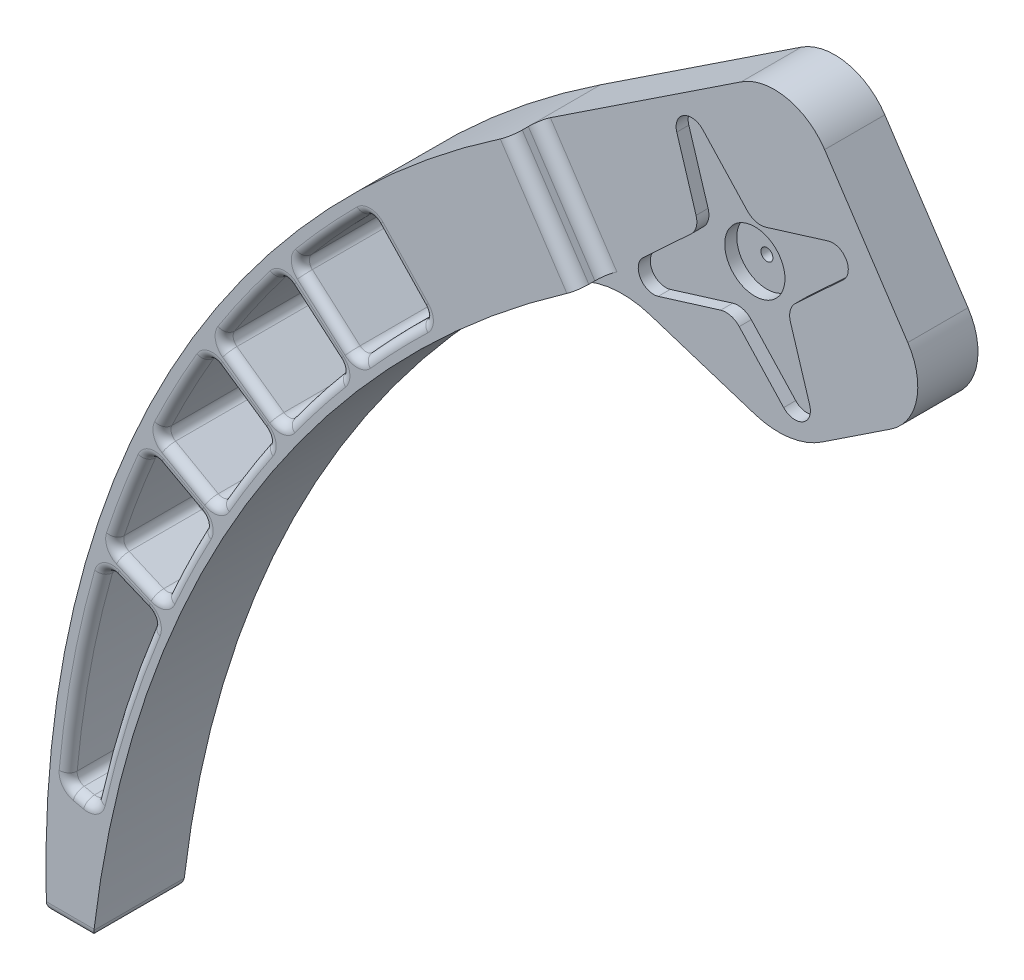
SolidWorks part; units mm, degrees
ref_plane "Plan de face" through (0, 0, 0) normal (0, 0, 1) x (1, 0, 0)
ref_plane "Plan de dessus" through (0, 0, 0) normal (0, 1, 0) x (1, 0, 0)
ref_plane "Plan de droite" through (0, 0, 0) normal (1, 0, 0) x (0, 0, -1)
sketch "Esquisse1" plane through (0, 0, 0) normal (0, 0, 1) x (1, 0, 0)
  line L0 (0, 0) -> (-7.7116, 0)
  line L1 (-7.7116, 0) -> (-7.7116, 150) construction
  line L2 (-7.7116, 150) -> (69.2884, 150) construction
  line L3 (69.2884, 150) -> (80.3349, 133.3274)
  arc A0 (-7.7116, 0) -> (69.2884, 150) centre (164.4344, 6.3951) cw
  arc A1 (80.3349, 133.3274) -> (0, 0) centre (185.1203, -20.676) ccw
  dimension "D1" = 20
  dimension "D2" = 150
  dimension "D3" = 77
extrude "Boss.-Extru.1" add sketch "Esquisse1" along normal blind 15
sketch "Esquisse2" plane through (0, 0, 15) normal (0, 0, 1) x (1, 0, 0)
  line L0 (80.3349, 133.3274) -> (69.2884, 150) construction
  line L1 (-7.7116, 0) -> (0, 0) construction
  line L2 (62.3684, 141.3979) -> (70.9664, 130.2035)
  line L3 (48.6033, 129.7481) -> (58.0983, 119.3958)
  line L4 (70.9454, 147.4991) -> (78.6779, 135.8283)
  line L5 (46.0039, 127.2473) -> (55.6406, 117.1018)
  line L6 (69.2884, 150) -> (70.9454, 147.4991)
  line L7 (78.6779, 135.8283) -> (80.3349, 133.3274)
  line L8 (-7.7116, 0) -> (-4.7116, 0)
  line L9 (-3, 0) -> (-4.7116, 0)
  line L10 (0, 0) -> (-3, 0)
  line L11 (33.8448, 113.9602) -> (43.9728, 105.0081)
  line L12 (31.5886, 111.1559) -> (41.7683, 102.4698)
  line L13 (21.2433, 96.4806) -> (31.4285, 89.2228)
  line L14 (19.3677, 93.4257) -> (29.5014, 86.4679)
  line L15 (10.9988, 77.6405) -> (20.603, 72.2126)
  line L16 (9.5313, 74.393) -> (18.9744, 69.2715)
  line L17 (3.2521, 57.7957) -> (11.6148, 54.1641)
  line L18 (2.2102, 54.4164) -> (10.3026, 51.0688)
  line L19 (-4.2431, 20.0283) -> (0.2206, 19.0409)
  arc A1 (78.6779, 135.8283) -> (-3, 0) centre (188.3019, -22.5641) ccw
  arc A2 (70.9454, 147.4991) -> (-4.7116, 0) centre (165.108, 6.0472) ccw
  arc A3 (69.2884, 150) -> (-7.7116, 0) centre (164.4344, 6.3951) ccw
  arc A4 (69.2884, 150) -> (-7.7116, 0) centre (164.4344, 6.3951) ccw construction
  arc A5 (0, 0) -> (80.3349, 133.3274) centre (185.1203, -20.676) cw
  point P0 (78.6779, 135.8283)
  point P1 (70.9454, 147.4991)
  point P4 (-4.7116, 0)
  point P5 (-3, 0)
  dimension "D13" = 1
  dimension "D14" = 5
  dimension "D15" = 1
  dimension "D1" = 3
  dimension "D2" = 3
  dimension "D3" = 3
  dimension "D4" = 3
  dimension "D5" = 4
  dimension "D6" = 5
  dimension "D7" = 1
  dimension "D8" = 5
  dimension "D9" = 1
  dimension "D10" = 5
  dimension "D11" = 1
  dimension "D12" = 5
  dimension "D16" = 10
extrude "Enlèv. mat.-Extru.3" cut sketch "Esquisse2" against normal up to next contours L2 A2 L3 A1 | L5 A2 L11 A1 | L12 A2 L13 A1 | L14 A2 L15 A1 | L16 A2 L17 A1 | L18 A2 L19 A1
sketch "Esquisse12" plane through (0, 0, 0) normal (0, 0, 1) x (1, 0, 0)
  line L0 (94.143, 112.4867) -> (69.2884, 150)
  line L1 (69.2884, 150) -> (110.9699, 177.6162)
  line L2 (110.9699, 177.6162) -> (135.8245, 140.1029)
  line L3 (135.8245, 140.1029) -> (94.143, 112.4867)
  dimension "D1" = 50
  dimension "D2" = 45
  dimension "D3" = 0
extrude "Boss.-Extru.4" add sketch "Esquisse12" along normal blind 10
sketch "Esquisse27" plane through (0, 0, 15) normal (0, 0, 1) x (1, 0, 0)
  line L0 (47.1881, 129.6841) -> (58.0565, 117.812)
  line L1 (58.0565, 117.812) -> (72.7204, 130.1897)
  line L2 (72.7204, 130.1897) -> (62.3562, 143.5699)
  line L3 (62.3562, 143.5699) -> (47.1881, 129.6841)
extrude "Boss.-Extru.5" add sketch "Esquisse27" against normal blind 15
fillet "Congé8" radius 10 2 edges at (135.8245, 140.1029, 5) (110.9699, 177.6162, 5)
fillet "Congé18" radius 2 1 edges at (74.8117, 141.6637, 10)
sketch "Esquisse24" plane through (82.6638, -34.6024, 10) normal (0, 0, 1) x (0.866, 0.5, 0)
  line L0 (107.5945, 145.7269) -> (90.416, 145.7269) construction
  line L1 (89.8462, 148.2269) -> (107.3962, 152.2269)
  line L2 (107.3962, 139.2269) -> (89.8462, 143.2269)
  arc A0 (107.3962, 139.2269) -> (107.3962, 152.2269) centre (107.5945, 145.7269) ccw
  arc A1 (89.8462, 148.2269) -> (89.8462, 143.2269) centre (90.416, 145.7269) ccw
  dimension "D1" = 18
  dimension "D2" = 13
  dimension "D3" = 5
extrude "Enlèv. mat.-Extru.9" cut sketch "Esquisse24" against normal blind 2
pattern_circular "Répétition circulaire1" count 4 over 270 about axis through (102.9798, 145.3981, 0) along (0, 0, 1) of "Enlèv. mat.-Extru.9"
sketch "Esquisse25" plane through (0, 0, 8) normal (0, 0, 1) x (1, 0, 0)
  circle A0 centre (102.9059, 145.4019) radius 1
  dimension "D1" = 2
extrude "Enlèv. mat.-Extru.10" cut sketch "Esquisse25" against normal through all
sketch "Esquisse26" plane through (0, 0, 10) normal (0, 0, 1) x (1, 0, 0)
  line L0 (80.3349, 133.3274) -> (94.143, 112.4867)
  line L1 (80.3349, 133.3274) -> (94.143, 112.4867) construction
  line L2 (94.143, 112.4867) -> (127.4882, 134.5797) construction
  line L3 (94.143, 112.4867) -> (110.8156, 123.5332)
  line L4 (110.8156, 123.5332) -> (80.3349, 133.3274)
  arc A0 (81.9945, 134.4436) -> (80.3349, 133.3274) centre (185.1203, -20.676) ccw construction
extrude "Enlèv. mat.-Extru.11" cut sketch "Esquisse26" against normal through all
fillet "Congé21" radius 3 4 edges at (110.2612, 143.447, 9) (104.9309, 152.6794, 9) (95.6985, 147.3491, 9) (101.0288, 138.1167, 9)
fillet "Congé22" radius 15 1 edges at (80.3349, 133.3274, 5)
fillet "Congé26" radius 13 1 edges at (110.8156, 123.5332, 5)
fillet "Congé27" radius 1.5 64 edges at (4.5624, 35.275, 0) (4.5624, 35.275, 15) (-1.9038, 37.3889, 15) (-1.9038, 37.3889, 0) (15.1298, 61.7981, 0) (6.1749, 66.1764, 0) (6.1749, 66.1764, 15) (15.1298, 61.7981, 15) (24.8967, 79.4374, 0) (24.8967, 79.4374, 15) (14.9756, 85.6432, 15) (14.9756, 85.6432, 0) (36.4539, 95.9591, 0) (26.222, 103.955, 0) (26.222, 103.955, 15) (36.4539, 95.9591, 15) (-7.7116, 0, 7.5) (-3.8558, 0, 15) (0, 0, 7.5) (-3.8558, 0, 0) (0.2206, 19.0409, 7.5) (-2.0112, 19.5346, 15) (-4.2431, 20.0283, 7.5) (-2.0112, 19.5346, 0) (11.6148, 54.1641, 7.5) (7.4334, 55.9799, 15) (3.2521, 57.7957, 7.5) (7.4334, 55.9799, 0) (14.2529, 71.8322, 0) (9.5313, 74.393, 7.5) (14.2529, 71.8322, 15) (18.9744, 69.2715, 7.5) (20.603, 72.2126, 7.5) (15.8009, 74.9266, 15) (10.9988, 77.6405, 7.5) (15.8009, 74.9266, 0) (31.4285, 89.2228, 7.5) (26.3359, 92.8517, 15) (21.2433, 96.4806, 7.5) (26.3359, 92.8517, 0) (36.6785, 106.8128, 0) (31.5886, 111.1559, 7.5) (36.6785, 106.8128, 15) (41.7683, 102.4698, 7.5) (49.6748, 111.1822, 0) (50.8223, 122.1745, 0) (39.7482, 120.765, 0) (49.6748, 111.1822, 15) (38.9088, 109.4842, 15) (39.7482, 120.765, 15) (50.8223, 122.1745, 15) (6.2564, 52.7426, 0) (2.2102, 54.4164, 7.5) (6.2564, 52.7426, 15) (10.3026, 51.0688, 7.5) (24.4346, 89.9468, 0) (19.3677, 93.4257, 7.5) (24.4346, 89.9468, 15) (29.5014, 86.4679, 7.5) (46.0039, 127.2473, 7.5) (55.6406, 117.1018, 7.5) (43.9728, 105.0081, 7.5) (33.8448, 113.9602, 7.5) (38.9088, 109.4842, 0)
fillet "Congé29" radius 2 1 edges at (74.8117, 141.6637, 15)
sketch "Esquisse29" plane through (0, 0, 8) normal (0, 0, 1) x (1, 0, 0)
  circle A0 centre (102.9059, 145.4019) radius 5
  dimension "D1" = 10
extrude "Enlèv. mat.-Extru.12" cut sketch "Esquisse29" against normal blind 2
